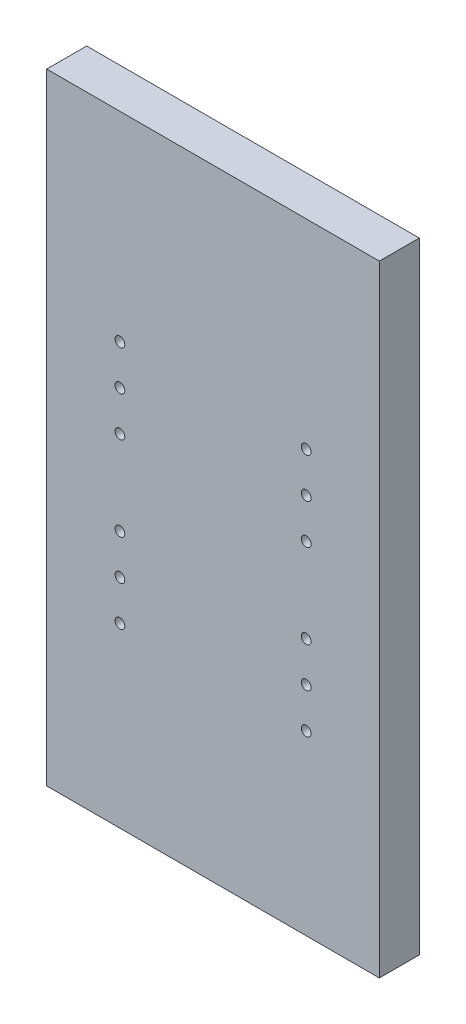
SolidWorks part; units mm, degrees
material "Maple"
ref_plane "Front Plane" through (0, 0, 0) normal (0, 0, 1) x (1, 0, 0)
ref_plane "Top Plane" through (0, 0, 0) normal (0, 1, 0) x (1, 0, 0)
ref_plane "Right Plane" through (0, 0, 0) normal (1, 0, 0) x (0, 0, -1)
sketch3d "3DSketch1"
  line L1 (296.0431, 1172.6929, 0) -> (146.0431, 1172.6929, 0)
  line L2 (296.0431, 1172.6929, 0) -> (296.0431, 892.6929, 0)
  line L3 (296.0431, 892.6929, 0) -> (146.0431, 892.6929, 0)
  line L4 (146.0431, 1172.6929, 0) -> (146.0431, 892.6929, 0)
  line L5 (296.0431, 1172.6929, 0) -> (146.0431, 892.6929, 0) construction
  line L6 (296.0431, 892.6929, 0) -> (146.0431, 1172.6929, 0) construction
  point P0 (221.0431, 1032.6929, 0)
  dimension "D1" = 280
  dimension "D2" = 150
extrude "Boss-Extrude1" add sketch "3DSketch1" along a picked direction on the side of the normal blind 18
sketch3d "3DSketch2"
  circle A0 centre (179.0431, 1082.6929, 21) radius 2.2 construction
  circle A1 centre (179.0431, 1082.6929, 21) radius 2.2
  circle A2 centre (179.0431, 1064.6929, 21) radius 2.2 construction
  circle A3 centre (179.0431, 1064.6929, 21) radius 2.2
  circle A4 centre (179.0431, 1046.6929, 21) radius 2.2 construction
  circle A5 centre (179.0431, 1046.6929, 21) radius 2.2
  circle A6 centre (179.0431, 1008.6929, 21) radius 2.2 construction
  circle A7 centre (179.0431, 1008.6929, 21) radius 2.2
  circle A8 centre (179.0431, 990.6929, 21) radius 2.2 construction
  circle A9 centre (179.0431, 990.6929, 21) radius 2.2
  circle A10 centre (179.0431, 972.6929, 21) radius 2.2 construction
  circle A11 centre (179.0431, 972.6929, 21) radius 2.2
  circle A12 centre (263.0431, 972.6929, 21) radius 2.2 construction
  circle A13 centre (263.0431, 972.6929, 21) radius 2.2
  circle A14 centre (263.0431, 990.6929, 21) radius 2.2 construction
  circle A15 centre (263.0431, 990.6929, 21) radius 2.2
  circle A16 centre (263.0431, 1008.6929, 21) radius 2.2 construction
  circle A17 centre (263.0431, 1008.6929, 21) radius 2.2
  circle A18 centre (263.0431, 1046.6929, 21) radius 2.2 construction
  circle A19 centre (263.0431, 1046.6929, 21) radius 2.2
  circle A20 centre (263.0431, 1082.6929, 21) radius 2.2 construction
  circle A21 centre (263.0431, 1082.6929, 21) radius 2.2
  circle A22 centre (263.0431, 1064.6929, 21) radius 2.2 construction
  circle A23 centre (263.0431, 1064.6929, 21) radius 2.2
  point P2 (179.0431, 1082.6929, 18.8)
  point P4 (179.0431, 1082.6929, 18.8)
  point P7 (179.0431, 1064.6929, 18.8)
  point P9 (179.0431, 1064.6929, 18.8)
  point P12 (179.0431, 1046.6929, 18.8)
  point P14 (179.0431, 1046.6929, 18.8)
  point P17 (179.0431, 1008.6929, 18.8)
  point P19 (179.0431, 1008.6929, 18.8)
  point P22 (179.0431, 990.6929, 18.8)
  point P24 (179.0431, 990.6929, 18.8)
  point P27 (179.0431, 972.6929, 18.8)
  point P29 (179.0431, 972.6929, 18.8)
  point P32 (263.0431, 972.6929, 18.8)
  point P34 (263.0431, 972.6929, 18.8)
  point P37 (263.0431, 990.6929, 18.8)
  point P39 (263.0431, 990.6929, 18.8)
  point P42 (263.0431, 1008.6929, 18.8)
  point P44 (263.0431, 1008.6929, 18.8)
  point P47 (263.0431, 1046.6929, 18.8)
  point P49 (263.0431, 1046.6929, 18.8)
  point P52 (263.0431, 1082.6929, 18.8)
  point P54 (263.0431, 1082.6929, 18.8)
  point P57 (263.0431, 1064.6929, 18.8)
  point P59 (263.0431, 1064.6929, 18.8)
extrude "Cut-Extrude1" cut sketch "3DSketch2" along a picked direction on the side of the normal blind 18 contours A19 | A23 | A21 | A1 | A3 | A5 | A7 | A9 | A11 | A13 | A15 | A17
